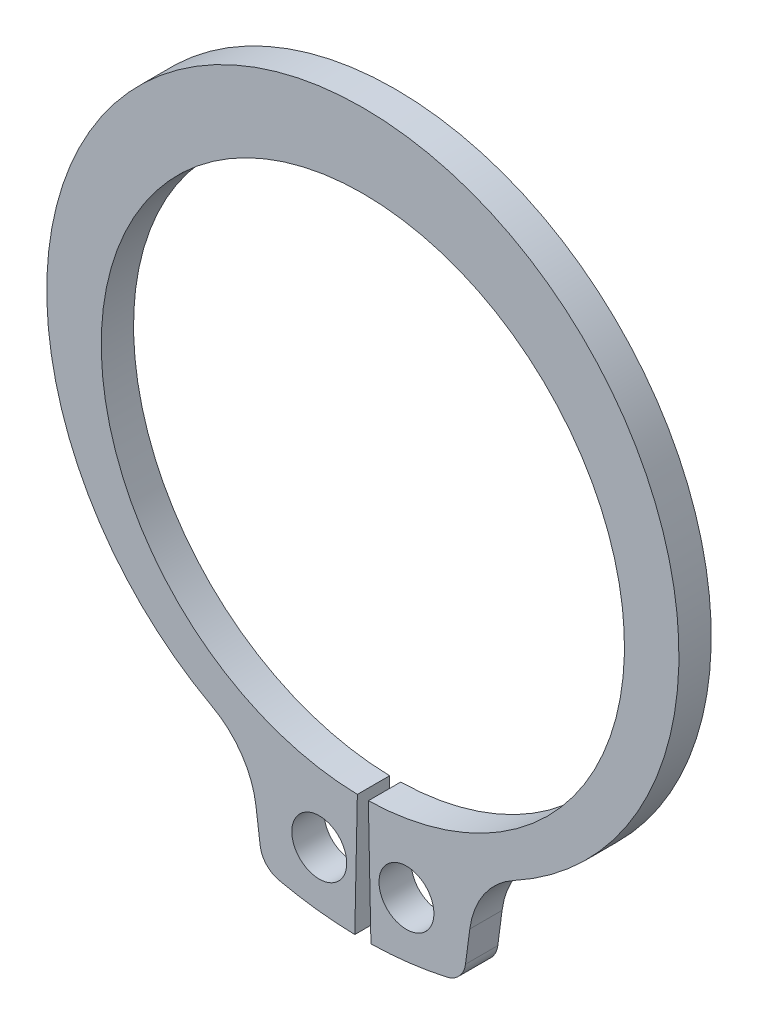
SolidWorks part; units mm, degrees
ref_plane "Plane1" through (0, 0, 0) normal (0, 0, 1) x (1, 0, 0)
ref_plane "Plane2" through (0, 0, 0) normal (0, 1, 0) x (1, 0, 0)
ref_plane "Plane3" through (0, 0, 0) normal (1, 0, 0) x (0, 0, -1)
extrude "Body" add sketch "BodySke" against normal blind 1
sketch "BodySke" plane through (0, 0, 0) normal (0, 0, 1) x (1, 0, 0)
  line L0 (-1.5431, 0) -> (1.5431, 0) construction
  line L1 (0, 0) -> (0, 10.4) construction
  line L2 (0.1702, -8.0982) -> (0.25, -11.8974)
  line L3 (-0.1702, -8.0982) -> (-0.25, -11.8974)
  line L4 (0, 0) -> (5.9372, -10.3131) construction
  line L5 (0, 0) -> (-5.9372, -10.3131) construction
  line L7 (3.3109, -9.9673) -> (3.1777, -10.979)
  line L8 (-3.3109, -9.9673) -> (-3.1777, -10.979)
  circle A0 centre (0, 0) radius 8.1 construction
  arc A1 (0.1702, -8.0982) -> (-0.1702, -8.0982) centre (0, 0) ccw
  arc A2 (4.6151, -8.0165) -> (-4.6151, -8.0165) centre (0, 0.6135) ccw construction
  arc A3 (0.25, -11.8974) -> (2.5979, -11.613) centre (0, 0) ccw
  arc A4 (4.6725, -7.9855) -> (3.3109, -9.9673) centre (5.9372, -10.3131) ccw
  arc A5 (-3.3109, -9.9673) -> (-4.6725, -7.9855) centre (-5.9372, -10.3131) ccw
  arc A6 (-2.5979, -11.613) -> (-0.25, -11.8974) centre (0, 0) ccw
  arc A7 (4.6725, -7.9855) -> (-4.6725, -7.9855) centre (0, 0.6135) ccw
  arc A8 (-3.355, -9.6324) -> (3.355, -9.6324) centre (0, 0) ccw construction
  circle A9 centre (1.35, -10.1103) radius 0.85
  circle A10 centre (-1.35, -10.1103) radius 0.85
  arc A11 (3.1777, -10.979) -> (2.5979, -11.613) centre (2.4341, -10.8811) cw
  arc A12 (-3.1777, -10.979) -> (-2.5979, -11.613) centre (-2.4341, -10.8811) ccw
  point P28 (3.1109, -11.4862)
  point P31 (-3.1109, -11.4862)
  dimension "GrooveDia" = 16.2
  dimension "D3" = 0.75
  dimension "LugRad" = 11.9
  dimension "HoleOffsetRad" = 10.2
  dimension "HoleDia" = 1.7
  dimension "D2" = 15
  dimension "LargeRad" = 10.4
  dimension "SmallRad" = 9.25
  dimension "Gap" = 0.5
  dimension "SmallAngle" = 59.858
  dimension "HoleSpacing" = 2.7
sketch "Clipboard" plane through (0, 0, 0) normal (0, 0, 1) x (1, 0, 0)
  line L0 (0, 0) -> (2.3, 0)
  line L1 (0, 0) -> (0, 1.15)
  line L2 (0, 0) -> (0, -3.8)
  circle A0 centre (0, 0) radius 0.85
  circle A1 centre (0, 0) radius 8.5
  dimension "HoleDia" = 1.7
  dimension "ShaftDia" = 17
  dimension "LargeSection" = 2.3
  dimension "SmallSection" = 1.15
  dimension "LugSection" = 3.8
sketch "NotSke" plane through (0, 0, 0) normal (0, 0, 1) x (1, 0, 0)
  line L0 (1.35, -9.2603) -> (1.35, -10.9603)
  line L1 (1.35, -10.9603) -> (-1.35, -10.9603)
  line L2 (-1.35, -10.9603) -> (-1.35, -9.2603)
  line L3 (-1.35, -9.2603) -> (1.35, -9.2603)
  circle A0 centre (1.35, -10.1103) radius 0.85 construction
  circle A1 centre (-1.35, -10.1103) radius 0.85 construction
extrude "Notch" [suppressed] cut sketch "NotSke" against normal through all
sketch "UnlSke" plane through (0, 0, 0) normal (0, 0, 1) x (1, 0, 0)
  line L0 (-2.5525, -11.623) -> (-1.7374, -7.9115)
  line L1 (2.5525, -11.623) -> (1.7374, -7.9115)
  arc A0 (1.7374, -7.9115) -> (-1.7374, -7.9115) centre (0, 0) ccw
  arc A1 (2.5525, -11.623) -> (-2.5525, -11.623) centre (0, 0) ccw
  arc A2 (0.25, -11.8974) -> (2.5979, -11.613) centre (0, 0) ccw construction
  arc A3 (0.1702, -8.0982) -> (-0.1702, -8.0982) centre (0, 0) ccw construction
  circle A4 centre (-1.35, -10.1103) radius 0.85 construction
  circle A5 centre (1.35, -10.1103) radius 0.85 construction
extrude "Unlug" [suppressed] add sketch "UnlSke" against normal through all
equation "' \"ShaftDia@Clipboard\" = 3"
equation "' \"Thickness@Body\" = 0.4"
equation "' \"GrooveDia@BodySke\" = 2.8"
equation "' \"LugSection@Clipboard\" = 1.9"
equation "' \"LargeSection@Clipboard\" = 0.8"
equation "' \"HoleDia@Clipboard\" = 1.0"
equation "' \"ShaftDia@Clipboard\" = 10"
equation "' \"Thickness@Body\" = 1.0"
equation "' \"GrooveDia@BodySke\" = 9.6"
equation "' \"LugSection@Clipboard\" = 3.3"
equation "' \"LargeSection@Clipboard\" = 1.8"
equation "' \"HoleDia@Clipboard\" = 1.5"
equation "\"SmallSection@Clipboard\" = \"LargeSection@Clipboard\" * 0.5"
equation "\"Gap@BodySke\" =  \"Thickness@Body\" / 2"
equation "\"LargeRad@BodySke\" =  \"GrooveDia@BodySke\" / 2 +  \"LargeSection@Clipboard\""
equation "\"SmallRad@BodySke\" =  \"GrooveDia@BodySke\" / 2 +  \"SmallSection@Clipboard\""
equation "\"LugRad@BodySke\" = \"GrooveDia@BodySke\" / 2 + \"LugSection@Clipboard\""
equation "\"HoleOffsetRad@BodySke\" = (  \"ShaftDia@Clipboard\" / 2 + \"LugRad@BodySke\" ) / 2"
equation "\"HoleSpacing@BodySke\" = \"Gap@BodySke\"  * 2 +  \"HoleDia@Clipboard\""
equation "\"HoleDia@BodySke\" =  \"HoleDia@Clipboard\""
equation "\"SmallAngle@BodySke\" = atn(\"HoleSpacing@BodySke\" / 2 / sqr(\"HoleOffsetRad@BodySke\"  * \"HoleOffsetRad@BodySke\" - (\"HoleSpacing@BodySke\" / 2) * (\"HoleSpacing@BodySke\" / 2) ))  * 7 *  (\"LargeRad@BodySke\" / \"SmallRad@BodySke\")* ( 180 / 3.141593)"
